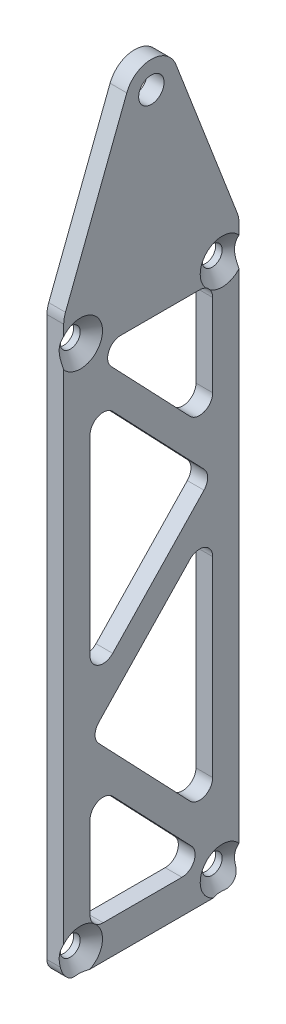
SolidWorks part; units mm, degrees
material "6061 Alloy"
ref_plane "Front Plane" through (0, 0, 0) normal (0, 0, 1) x (1, 0, 0)
ref_plane "Top Plane" through (0, 0, 0) normal (0, 1, 0) x (1, 0, 0)
ref_plane "Right Plane" through (0, 0, 0) normal (1, 0, 0) x (0, 0, -1)
sketch "Sketch1" plane through (0, 0, 0) normal (1, 0, 0) x (0, 0, -1)
  line L0 (-13.4747, 0) -> (13.4747, 0) construction
  line L1 (0, 0) -> (0, 35) construction
  line L2 (-13.4747, 0) -> (0, 35) construction
  line L3 (0, 35) -> (13.4747, 0) construction
  line L4 (13.4747, 0) -> (-13.4747, 0) construction
  line L5 (20.7574, -5) -> (-20.7574, -5)
  line L6 (-20.7574, -5) -> (0, 48.9165)
  line L7 (0, 48.9165) -> (20.7574, -5)
  line L8 (-13.4747, 0) -> (13.4747, 0) construction
  line L9 (-13.4747, 0) -> (-13.4747, -100) construction
  line L10 (13.4747, 0) -> (13.4747, -100) construction
  line L11 (-13.4747, -100) -> (13.4747, -100) construction
  line L12 (-20.7574, -5) -> (20.7574, -5)
  line L13 (-20.7574, -5) -> (-20.7574, -103.81)
  line L14 (20.7574, -5) -> (20.7574, -103.81)
  line L15 (-20.7574, -103.81) -> (20.7574, -103.81)
  circle A0 centre (-13.4747, 0) radius 1.8288
  circle A1 centre (0, 35) radius 2.413
  circle A2 centre (13.4747, 0) radius 1.8288
  circle A3 centre (-13.4747, -100) radius 1.8288
  circle A4 centre (13.4747, -100) radius 1.8288
  point P4 (0, 0)
  dimension "D3" = 3.6576
  dimension "D4" = 4.826
  dimension "D1" = 26.9494
  dimension "D5" = 100
  dimension "D6" = 3.81
  dimension "D7" = 35
  dimension "D2" = 5
extrude "Boss-Extrude1" add sketch "Sketch1" along normal blind 3.175 contours L13 L15 L14 L5 A4 A3 | L7 L6 L5 A2 A1 A0 | A0 | A2 | A4 | A3
sketch "Sketch2" plane through (3.175, 0, 0) normal (1, 0, 0) x (0, 0, -1)
  line L3 (-11.645, -97.42) -> (-11.645, -2.5) construction
  line L4 (11.645, -97.42) -> (11.645, -2.5) construction
  line L5 (-11.645, -2.5) -> (11.645, -2.5) construction
  line L6 (-11.645, -97.42) -> (11.645, -97.42) construction
  line L7 (-20.7574, -5) -> (-20.7574, -103.81) construction
  line L9 (11.645, -2.5) -> (-11.645, -2.5)
  line L10 (-11.645, -2.5) -> (11.645, -26.8987)
  line L11 (11.645, -26.8987) -> (11.645, -2.5)
  line L12 (-11.645, -9.7413) -> (11.645, -34.14)
  line L13 (11.645, -34.14) -> (-11.645, -58.5387)
  line L14 (-11.645, -58.5387) -> (-11.645, -34.14)
  line L15 (11.645, -37.7607) -> (-11.645, -62.1593) construction
  line L16 (-11.645, -34.14) -> (-11.645, -9.7413)
  line L17 (-11.645, -73.0213) -> (-11.645, -97.42)
  line L18 (-11.645, -97.42) -> (11.645, -97.42)
  line L19 (11.645, -97.42) -> (-11.645, -73.0213)
  line L20 (11.645, -41.3813) -> (11.645, -65.78)
  line L21 (11.645, -65.78) -> (11.645, -90.1787)
  line L22 (11.645, -90.1787) -> (-11.645, -65.78)
  line L23 (-11.645, -65.78) -> (11.645, -41.3813)
  line L24 (-16.645, -1051.4901) -> (-16.645, 48948.5099) construction
  line L25 (16.645, -1047.4882) -> (16.645, 48952.5118) construction
  line L26 (-20.7574, -5) -> (-16.645, -5) construction
  line L27 (20.7574, -5) -> (16.645, -5) construction
  line L28 (-16.645, -103.81) -> (-16.645, 37.413)
  line L29 (-16.645, -103.81) -> (-20.7574, -103.81)
  line L30 (-16.645, 37.413) -> (-20.7574, 37.413)
  line L31 (-20.7574, -103.81) -> (-20.7574, 37.413)
  line L32 (-20.7574, -103.81) -> (20.7574, -103.81) construction
  line L33 (16.645, -103.81) -> (16.645, 37.413)
  line L34 (16.645, -103.81) -> (20.7574, -103.81)
  line L35 (16.645, 37.413) -> (20.7574, 37.413)
  line L36 (20.7574, -103.81) -> (20.7574, 37.413)
  circle A2 centre (0, 35) radius 2.413 construction
  point P0 (11.645, -49.96)
  point P2 (0, -97.42)
  point P28 (0, -49.96)
  dimension "D4" = 2.58
  dimension "D1" = 33.29
  dimension "D2" = 5
  dimension "D3" = 2.5
  dimension "D5" = 5
  dimension "D6" = 2.5
  dimension "D7" = 2
  dimension "D8" = 5
extrude "Cut-Extrude1" cut sketch "Sketch2" against normal through all
fillet "Fillet1" radius 2.5 14 edges at (1.5875, -97.42, -11.645) (1.5875, -90.1787, -11.645) (1.5875, -41.3813, -11.645) (1.5875, -73.0213, 11.645) (1.5875, -97.42, 11.645) (1.5875, -65.78, 11.645) (1.5875, -58.5387, 11.645) (1.5875, -34.14, -11.645) (1.5875, -9.7413, 11.645) (1.5875, -2.5, 11.645) (1.5875, -26.8987, -11.645) (1.5875, -2.5, -11.645) (1.5875, -103.81, 16.645) (1.5875, -103.81, -16.645)
fillet "Fillet2" radius 5 3 edges at (1.5875, 48.9165, 0) (1.5875, 5.6818, 16.645) (1.5875, 5.6818, -16.645)
hole_wizard "CSK for #6 Flat Head Machine Screw (100)1" positions "Sketch3" profile "Sketch4" countersink size "#6" standard "ANSI Inch" end condition up to next
sketch "Sketch3" plane through (3.175, 0, 0) normal (1, 0, 0) x (0, 0, -1)
  point P0 (-13.4747, 0)
  point P3 (13.4747, 0)
  point P6 (13.4747, -100)
  point P9 (-13.4747, -100)
sketch "Sketch4" plane through (3.175, 0, 13.4747) normal (0, 1, 0) x (0, 0, -1)
  line L0 (0, 0) -> (0, 3.175)
  line L1 (0, 3.175) -> (1.8986, 3.175)
  line L2 (1.8986, 3.175) -> (1.8986, 1.93)
  line L3 (1.8986, 1.93) -> (4.1988, 0)
  line L5 (4.1988, 0) -> (0, 0)
  line L6 (-1.8986, 1.93) -> (-4.1988, 0) construction
  line L11 (0, -6.35) -> (0, 107.95) construction
  dimension "Thru Hole Dia." = 3.7973
  dimension "Thru Hole Depth" = 3.175
  dimension "Near C'Sink Dia." = 8.3975
  dimension "Near C'Sink Angle" = 100
